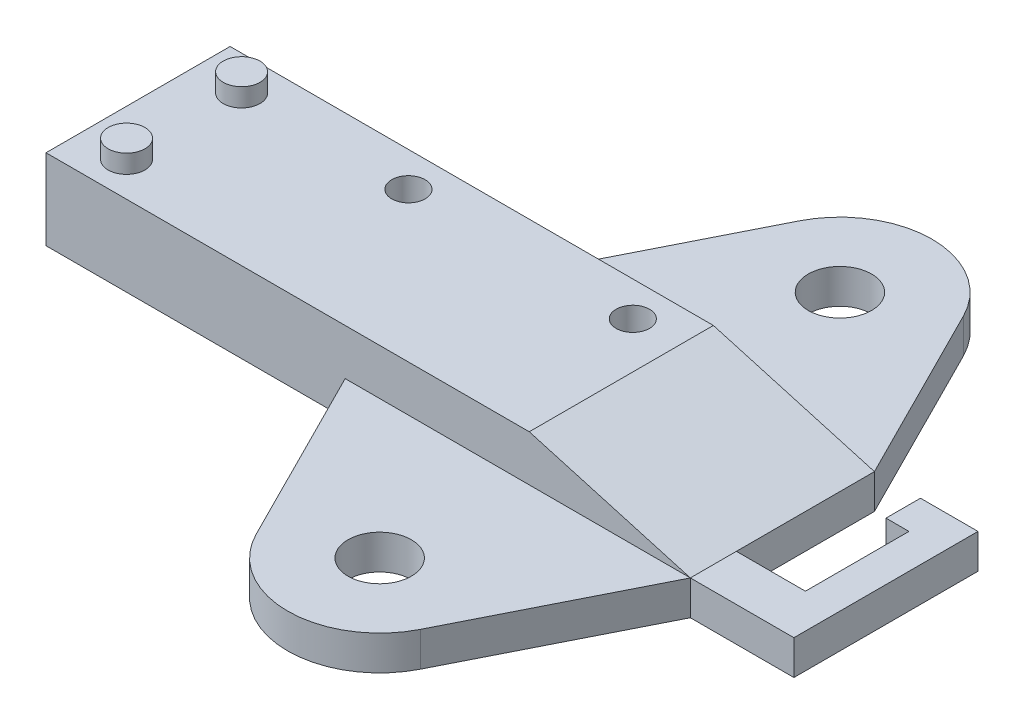
SolidWorks part; units mm, degrees
ref_plane "Front Plane" through (0, 0, 0) normal (0, 0, 1) x (1, 0, 0)
ref_plane "Top Plane" through (0, 0, 0) normal (0, 1, 0) x (1, 0, 0)
ref_plane "Right Plane" through (0, 0, 0) normal (1, 0, 0) x (0, 0, -1)
sketch "Sketch1" plane through (0, 0, 0) normal (0, 1, 0) x (1, 0, 0)
  line L1 (-21, 8) -> (21, 8)
  line L2 (-21, 8) -> (-21, -8)
  line L3 (-21, -8) -> (21, -8)
  line L4 (21, 8) -> (21, -8)
  line L5 (-21, 8) -> (21, -8) construction
  line L6 (-21, -8) -> (21, 8) construction
  point P0 (0, 0)
  dimension "D1" = 42
  dimension "D2" = 16
extrude "Boss-Extrude1" add sketch "Sketch1" along normal blind 7
sketch "Sketch2" plane through (0, 7, 0) normal (0, 1, 0) x (1, 0, 0)
  line L0 (21, 8) -> (-21, 8) construction
  line L1 (-21, -8) -> (21, -8) construction
  line L2 (-21, 8) -> (-21, -8) construction
  circle A0 centre (-17, 5) radius 1.6
  circle A1 centre (-17, -5) radius 1.6
  dimension "D1" = 3.2
  dimension "D2" = 3.2
  dimension "D3" = 3
  dimension "D4" = 3
  dimension "D5" = 4
  dimension "D6" = 4
extrude "Boss-Extrude2" add sketch "Sketch2" along normal blind 1.6
sketch "Sketch3" plane through (0, 0, 0) normal (0, 1, 0) x (1, 0, 0)
  line L0 (21, -8) -> (21, 8) construction
  line L1 (21, 8) -> (-21, 8) construction
  line L2 (-21, 8) -> (-21, -8) construction
  circle A0 centre (-2.5, 5) radius 1.45
  circle A1 centre (17, 5) radius 1.45
  dimension "D5" = 2.9
  dimension "D6" = 2.9
  dimension "D1" = 4
  dimension "D2" = 3
  dimension "D3" = 3
  dimension "D4" = 18.5
extrude "Cut-Extrude1" cut sketch "Sketch3" along normal up to next
sketch "Sketch4" plane through (0, 0, 0) normal (0, 1, 0) x (1, 0, 0)
  line L0 (12.8548, 23.5981) -> (5, 8)
  line L1 (21, 8) -> (-21, 8) construction
  line L2 (5, 8) -> (35, 8)
  line L3 (35, 8) -> (27.1452, 23.5981)
  line L4 (21, -8) -> (21, 8) construction
  line L5 (-22.0212, 0) -> (26.8745, 0) construction
  line L6 (-4.73, 0) -> (4.73, 0) construction
  line L7 (35, -8) -> (27.1452, -23.5981)
  line L8 (5, -8) -> (35, -8)
  line L9 (12.8548, -23.5981) -> (5, -8)
  arc A0 (27.1452, 23.5981) -> (12.8548, 23.5981) centre (20, 20) ccw
  circle A1 centre (20, 20) radius 2.75
  circle A2 centre (20, -20) radius 2.75
  arc A3 (27.1452, -23.5981) -> (12.8548, -23.5981) centre (20, -20) cw
  dimension "D1" = 8
  dimension "D5" = 5.5
  dimension "D2" = 1
  dimension "D3" = 30
  dimension "D4" = 12
  dimension "D6" = 14
extrude "Boss-Extrude3" add sketch "Sketch4" along normal blind 3
sketch "Sketch5" plane through (0, 0, 0) normal (0, 0, 1) x (1, 0, 0)
  line L0 (21, 7) -> (35, 3)
  line L1 (35, 3) -> (35, 0)
  line L2 (8.8, 0) -> (-8.8, 0) construction
  line L3 (35, 3) -> (35, 0) construction
  line L4 (35, 0) -> (21, 0)
  line L5 (21, 0) -> (21, 7)
extrude "Boss-Extrude4" add sketch "Sketch5" along normal mid plane 16
sketch "Sketch6" plane through (0, 0, 0) normal (0, 1, 0) x (1, 0, 0)
  line L0 (35, -8) -> (44, -8)
  line L1 (44, -8) -> (44, 8)
  line L2 (44, 8) -> (39, 8)
  line L3 (39, 8) -> (39, 5)
  line L4 (39, 5) -> (41, 5)
  line L5 (41, 5) -> (41, -4)
  line L6 (41, -4) -> (35, -4)
  line L7 (35, -8) -> (35, 8) construction
  line L8 (35, -4) -> (35, -8)
  dimension "D1" = 16
  dimension "D2" = 4
  dimension "D3" = 3
  dimension "D4" = 5
  dimension "D5" = 9
  dimension "D6" = 2
extrude "Boss-Extrude5" add sketch "Sketch6" along normal blind 3
